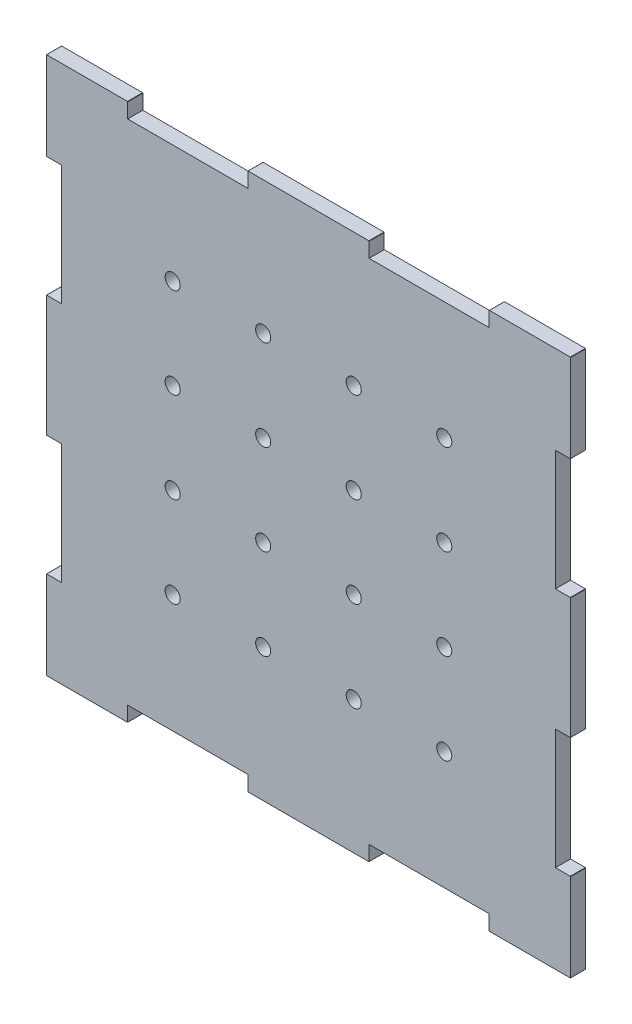
SolidWorks part; units mm, degrees
material "Acrylic (Medium-high impact)"
ref_plane "Front Plane" through (0, 0, 0) normal (0, 0, 1) x (1, 0, 0)
ref_plane "Top Plane" through (0, 0, 0) normal (0, 1, 0) x (1, 0, 0)
ref_plane "Right Plane" through (0, 0, 0) normal (1, 0, 0) x (0, 0, -1)
sketch "Model" plane through (0, 0, 0) normal (0, 0, 1) x (1, 0, 0)
  line L0 (-59.94, -89.08) -> (-59.93, -89.07)
  line L1 (-59.93, -89.07) -> (-59.92, -89.05)
  line L2 (-59.92, -89.05) -> (-59.91, -89.04)
  line L3 (-59.91, -89.04) -> (-59.9, -89.02)
  line L4 (-59.9, -89.02) -> (-59.9, -84.1)
  line L5 (-59.9, -84.1) -> (-20.1, -84.1)
  line L6 (-20.1, -84.1) -> (-20.1, -89.02)
  line L7 (-20.1, -89.02) -> (-20.08, -89.06)
  line L8 (-20.08, -89.06) -> (-20.07, -89.07)
  line L9 (-20.07, -89.07) -> (-20.05, -89.08)
  line L10 (-20.05, -89.08) -> (-20.04, -89.09)
  line L11 (-20.04, -89.09) -> (-20.02, -89.1)
  line L12 (-20.02, -89.1) -> (20.02, -89.1)
  line L13 (20.02, -89.1) -> (20.06, -89.08)
  line L14 (20.06, -89.08) -> (20.07, -89.07)
  line L15 (20.07, -89.07) -> (20.08, -89.05)
  line L16 (20.08, -89.05) -> (20.09, -89.04)
  line L17 (20.09, -89.04) -> (20.1, -89.02)
  line L18 (20.1, -89.02) -> (20.1, -84.1)
  line L19 (20.1, -84.1) -> (59.9, -84.1)
  line L20 (59.9, -84.1) -> (59.9, -89.02)
  line L21 (59.9, -89.02) -> (59.92, -89.06)
  line L22 (59.92, -89.06) -> (59.93, -89.07)
  line L23 (59.93, -89.07) -> (59.95, -89.08)
  line L24 (59.95, -89.08) -> (59.96, -89.09)
  line L25 (59.96, -89.09) -> (59.98, -89.1)
  line L26 (59.98, -89.1) -> (86.77, -89.1)
  line L27 (86.77, -89.1) -> (86.81, -89.08)
  line L28 (86.81, -89.08) -> (86.82, -89.07)
  line L29 (86.82, -89.07) -> (86.83, -89.05)
  line L30 (86.83, -89.05) -> (86.84, -89.04)
  line L31 (86.84, -89.04) -> (86.85, -89.02)
  line L32 (86.85, -89.02) -> (86.85, -59.98)
  line L33 (86.85, -59.98) -> (86.83, -59.94)
  line L34 (86.83, -59.94) -> (86.82, -59.93)
  line L35 (86.82, -59.93) -> (86.8, -59.92)
  line L36 (86.8, -59.92) -> (86.79, -59.91)
  line L37 (86.79, -59.91) -> (86.77, -59.9)
  line L38 (86.77, -59.9) -> (81.85, -59.9)
  line L39 (81.85, -59.9) -> (81.85, -20.1)
  line L40 (81.85, -20.1) -> (86.77, -20.1)
  line L41 (86.77, -20.1) -> (86.81, -20.08)
  line L42 (86.81, -20.08) -> (86.82, -20.07)
  line L43 (86.82, -20.07) -> (86.83, -20.05)
  line L44 (86.83, -20.05) -> (86.84, -20.04)
  line L45 (86.84, -20.04) -> (86.85, -20.02)
  line L46 (86.85, -20.02) -> (86.85, 20.02)
  line L47 (86.85, 20.02) -> (86.83, 20.06)
  line L48 (86.83, 20.06) -> (86.82, 20.07)
  line L49 (86.82, 20.07) -> (86.8, 20.08)
  line L50 (86.8, 20.08) -> (86.79, 20.09)
  line L51 (86.79, 20.09) -> (86.77, 20.1)
  line L52 (86.77, 20.1) -> (81.85, 20.1)
  line L53 (81.85, 20.1) -> (81.85, 59.9)
  line L54 (81.85, 59.9) -> (86.77, 59.9)
  line L55 (86.77, 59.9) -> (86.81, 59.92)
  line L56 (86.81, 59.92) -> (86.82, 59.93)
  line L57 (86.82, 59.93) -> (86.83, 59.95)
  line L58 (86.83, 59.95) -> (86.84, 59.96)
  line L59 (86.84, 59.96) -> (86.85, 59.98)
  line L60 (86.85, 59.98) -> (86.85, 89.02)
  line L61 (86.85, 89.02) -> (86.83, 89.06)
  line L62 (86.83, 89.06) -> (86.82, 89.07)
  line L63 (86.82, 89.07) -> (86.8, 89.08)
  line L64 (86.8, 89.08) -> (86.79, 89.09)
  line L65 (86.79, 89.09) -> (86.77, 89.1)
  line L66 (86.77, 89.1) -> (59.98, 89.1)
  line L67 (59.98, 89.1) -> (59.94, 89.08)
  line L68 (59.94, 89.08) -> (59.93, 89.07)
  line L69 (59.93, 89.07) -> (59.92, 89.05)
  line L70 (59.92, 89.05) -> (59.91, 89.04)
  line L71 (59.91, 89.04) -> (59.9, 89.02)
  line L72 (59.9, 89.02) -> (59.9, 84.1)
  line L73 (59.9, 84.1) -> (20.1, 84.1)
  line L74 (20.1, 84.1) -> (20.1, 89.02)
  line L75 (20.1, 89.02) -> (20.08, 89.06)
  line L76 (20.08, 89.06) -> (20.07, 89.07)
  line L77 (20.07, 89.07) -> (20.05, 89.08)
  line L78 (20.05, 89.08) -> (20.04, 89.09)
  line L79 (20.04, 89.09) -> (20.02, 89.1)
  line L80 (20.02, 89.1) -> (-20.02, 89.1)
  line L81 (-20.02, 89.1) -> (-20.06, 89.08)
  line L82 (-20.06, 89.08) -> (-20.07, 89.07)
  line L83 (-20.07, 89.07) -> (-20.08, 89.05)
  line L84 (-20.08, 89.05) -> (-20.09, 89.04)
  line L85 (-20.09, 89.04) -> (-20.1, 89.02)
  line L86 (-20.1, 89.02) -> (-20.1, 84.1)
  line L87 (-20.1, 84.1) -> (-59.9, 84.1)
  line L88 (-59.9, 84.1) -> (-59.9, 89.02)
  line L89 (-59.9, 89.02) -> (-59.92, 89.06)
  line L90 (-59.92, 89.06) -> (-59.93, 89.07)
  line L91 (-59.93, 89.07) -> (-59.95, 89.08)
  line L92 (-59.95, 89.08) -> (-59.96, 89.09)
  line L93 (-59.96, 89.09) -> (-59.98, 89.1)
  line L94 (-59.98, 89.1) -> (-86.77, 89.1)
  line L95 (-86.77, 89.1) -> (-86.81, 89.08)
  line L96 (-86.81, 89.08) -> (-86.82, 89.07)
  line L97 (-86.82, 89.07) -> (-86.83, 89.05)
  line L98 (-86.83, 89.05) -> (-86.84, 89.04)
  line L99 (-86.84, 89.04) -> (-86.85, 89.02)
  line L100 (-86.85, 89.02) -> (-86.85, 59.98)
  line L101 (-86.85, 59.98) -> (-86.83, 59.94)
  line L102 (-86.83, 59.94) -> (-86.82, 59.93)
  line L103 (-86.82, 59.93) -> (-86.8, 59.92)
  line L104 (-86.8, 59.92) -> (-86.79, 59.91)
  line L105 (-86.79, 59.91) -> (-86.77, 59.9)
  line L106 (-86.77, 59.9) -> (-81.85, 59.9)
  line L107 (-81.85, 59.9) -> (-81.85, 20.1)
  line L108 (-81.85, 20.1) -> (-86.77, 20.1)
  line L109 (-86.77, 20.1) -> (-86.81, 20.08)
  line L110 (-86.81, 20.08) -> (-86.82, 20.07)
  line L111 (-86.82, 20.07) -> (-86.83, 20.05)
  line L112 (-86.83, 20.05) -> (-86.84, 20.04)
  line L113 (-86.84, 20.04) -> (-86.85, 20.02)
  line L114 (-86.85, 20.02) -> (-86.85, -20.02)
  line L115 (-86.85, -20.02) -> (-86.83, -20.06)
  line L116 (-86.83, -20.06) -> (-86.82, -20.07)
  line L117 (-86.82, -20.07) -> (-86.8, -20.08)
  line L118 (-86.8, -20.08) -> (-86.79, -20.09)
  line L119 (-86.79, -20.09) -> (-86.77, -20.1)
  line L120 (-86.77, -20.1) -> (-81.85, -20.1)
  line L121 (-81.85, -20.1) -> (-81.85, -59.9)
  line L122 (-81.85, -59.9) -> (-86.77, -59.9)
  line L123 (-86.77, -59.9) -> (-86.81, -59.92)
  line L124 (-86.81, -59.92) -> (-86.82, -59.93)
  line L125 (-86.82, -59.93) -> (-86.83, -59.95)
  line L126 (-86.83, -59.95) -> (-86.84, -59.96)
  line L127 (-86.84, -59.96) -> (-86.85, -59.98)
  line L128 (-86.85, -59.98) -> (-86.85, -89.02)
  line L129 (-86.85, -89.02) -> (-86.83, -89.06)
  line L130 (-86.83, -89.06) -> (-86.82, -89.07)
  line L131 (-86.82, -89.07) -> (-86.8, -89.08)
  line L132 (-86.8, -89.08) -> (-86.79, -89.09)
  line L133 (-86.79, -89.09) -> (-86.77, -89.1)
  line L134 (-86.77, -89.1) -> (-59.98, -89.1)
  line L135 (-59.98, -89.1) -> (-59.94, -89.08)
extrude "Boss-Extrude1" add sketch "Model" along normal blind 5
sketch "Sketch2" plane through (0, 0, 5) normal (0, 0, 1) x (1, 0, 0)
  line L0 (45, -45) -> (-45, 45) construction
  line L1 (45, 45) -> (-45, -45) construction
  circle A0 centre (-45, 45) radius 2.5
  circle A1 centre (-15, 45) radius 2.5
  circle A2 centre (15, 45) radius 2.5
  circle A3 centre (45, 45) radius 2.5
  circle A4 centre (-15, 15) radius 2.5
  circle A5 centre (15, 15) radius 2.5
  circle A6 centre (45, 15) radius 2.5
  circle A7 centre (-15, -15) radius 2.5
  circle A8 centre (15, -15) radius 2.5
  circle A9 centre (45, -15) radius 2.5
  circle A10 centre (-15, -45) radius 2.5
  circle A11 centre (15, -45) radius 2.5
  circle A12 centre (45, -45) radius 2.5
  circle A13 centre (-45, 15) radius 2.5
  circle A14 centre (-45, -15) radius 2.5
  circle A15 centre (-45, -45) radius 2.5
  point P0 (0, 0)
  dimension "D3" = 5
  dimension "D1" = 90
  dimension "D2" = 90
extrude "Cut-Extrude1" cut sketch "Sketch2" against normal through all
